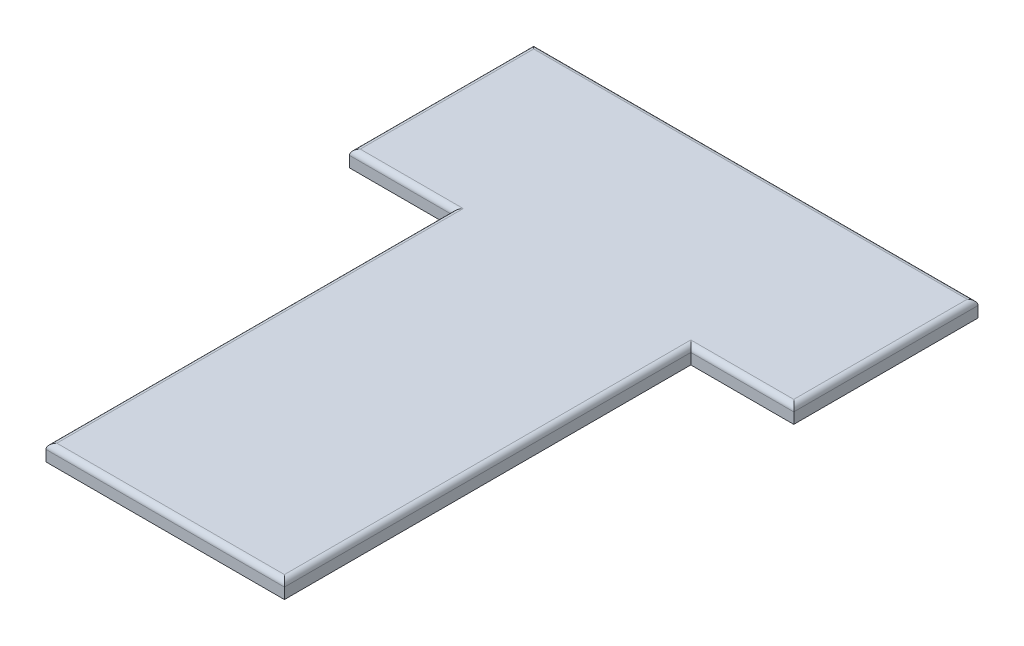
SolidWorks part; units mm, degrees
material "PF"
ref_plane "Front Plane" through (0, 0, 0) normal (0, 0, 1) x (1, 0, 0)
ref_plane "Top Plane" through (0, 0, 0) normal (0, 1, 0) x (1, 0, 0)
ref_plane "Right Plane" through (0, 0, 0) normal (1, 0, 0) x (0, 0, -1)
sketch "Sketch1" plane through (0, 0, 0) normal (0, 1, 0) x (1, 0, 0)
  line L0 (0, 0) -> (19, 0) construction
  line L1 (19, 0) -> (19, 75)
  line L2 (19, 75) -> (0, 75)
  line L3 (0, 75) -> (0, 109)
  line L4 (0, 109) -> (82, 109)
  line L5 (82, 109) -> (82, 75)
  line L6 (82, 75) -> (63, 75)
  line L7 (63, 75) -> (63, 0)
  line L8 (63, 0) -> (19, 0)
  dimension "D1" = 19
  dimension "D2" = 75
  dimension "D3" = 82
  dimension "D4" = 34
extrude "Boss-Extrude1" add sketch "Sketch1" along normal blind 3
fillet "Fillet2" radius 1 8 edges at (41, 3, -109) (82, 3, -92) (72.5, 3, -75) (63, 3, -37.5) (41, 3, 0) (19, 3, -37.5) (9.5, 3, -75) (0, 3, -92)
